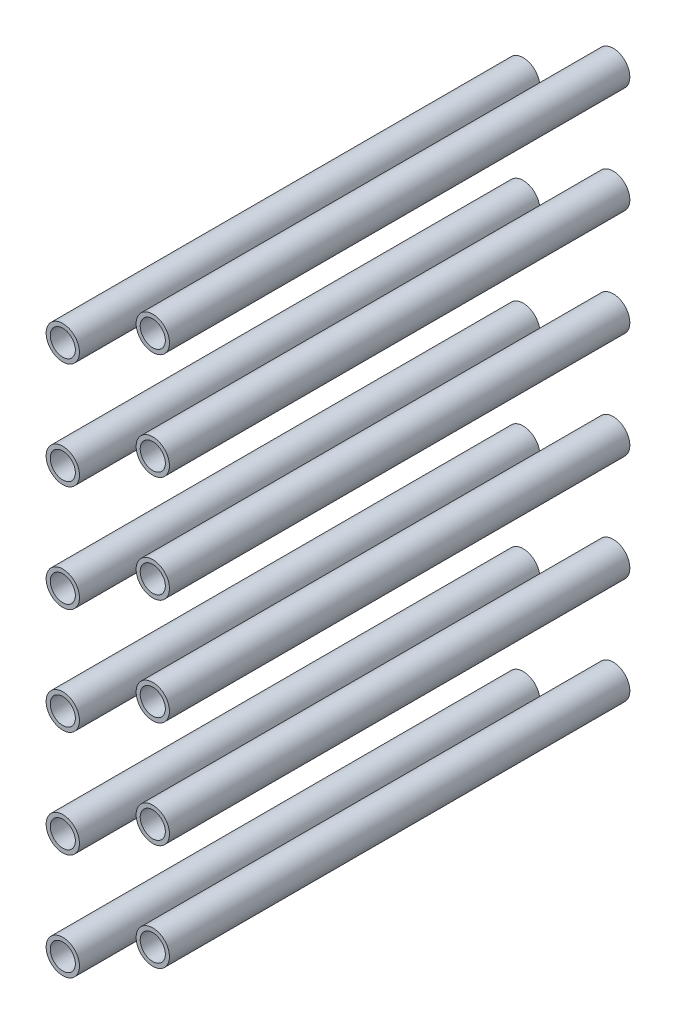
SolidWorks part; units mm, degrees
ref_plane "Front" through (0, 0, 0) normal (0, 0, 1) x (1, 0, 0)
ref_plane "Top" through (0, 0, 0) normal (0, 1, 0) x (1, 0, 0)
ref_plane "Right" through (0, 0, 0) normal (1, 0, 0) x (0, 0, -1)
sketch "Esboço1" plane through (0, 0, 0) normal (0, 0, 1) x (1, 0, 0)
  circle A28 centre (0, 0) radius 3
  circle A29 centre (0, 0) radius 3.98
  circle A30 centre (21.5, 12.7) radius 3
  circle A31 centre (21.5, 12.7) radius 3.98
  circle A32 centre (0, 25.4) radius 3.98
  circle A33 centre (0, 50.8) radius 3.98
  circle A34 centre (0, 76.2) radius 3.98
  circle A35 centre (0, 101.6) radius 3.98
  circle A36 centre (0, 127) radius 3.98
  circle A37 centre (21.5, 38.1) radius 3.98
  circle A38 centre (21.5, 38.1) radius 3
  circle A39 centre (21.5, 63.5) radius 3.98
  circle A40 centre (21.5, 63.5) radius 3
  circle A41 centre (21.5, 88.9) radius 3.98
  circle A42 centre (21.5, 88.9) radius 3
  circle A43 centre (21.5, 114.3) radius 3.98
  circle A44 centre (21.5, 114.3) radius 3
  circle A45 centre (21.5, 139.7) radius 3.98
  circle A46 centre (21.5, 139.7) radius 3
  circle A47 centre (0, 25.4) radius 3
  circle A48 centre (0, 50.8) radius 3
  circle A49 centre (0, 76.2) radius 3
  circle A50 centre (0, 101.6) radius 3
  circle A51 centre (0, 127) radius 3
  dimension "D1" = 6
  dimension "D3" = 6
  dimension "D2" = 6
extrude "Ressalto-extrusão1" add sketch "Esboço1" against normal blind 110
